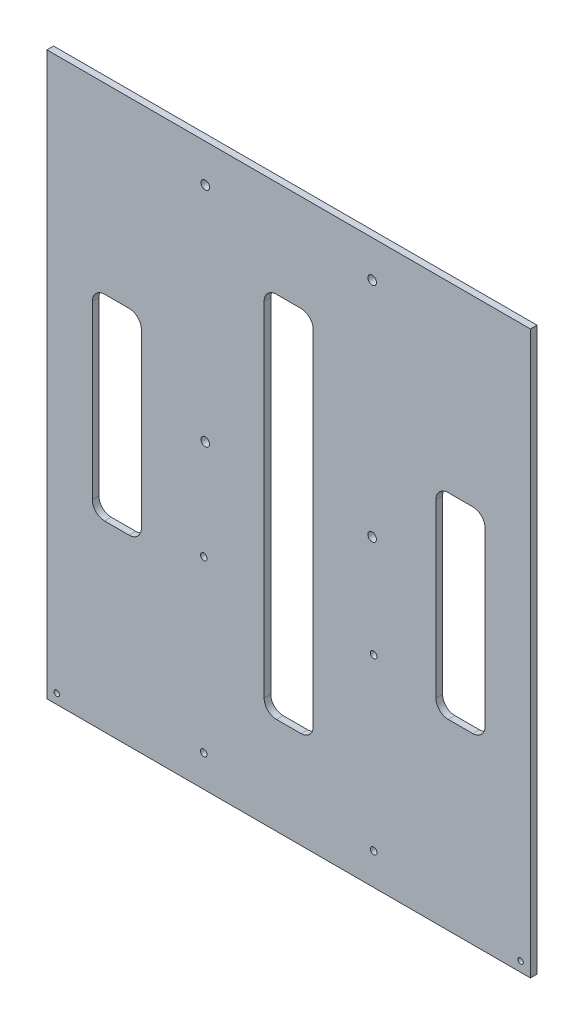
SolidWorks part; units mm, degrees
ref_plane "前视基准面" through (0, 0, 0) normal (0, 0, 1) x (1, 0, 0)
ref_plane "上视基准面" through (0, 0, 0) normal (0, 1, 0) x (1, 0, 0)
ref_plane "右视基准面" through (0, 0, 0) normal (1, 0, 0) x (0, 0, -1)
other "Configuration Table"
sketch "草图1" plane through (0, 0, 0) normal (0, 0, 1) x (1, 0, 0)
  line L1 (0, 0) -> (197, 0)
  line L2 (0, 0) -> (0, 229)
  line L3 (0, 229) -> (197, 229)
  line L4 (197, 0) -> (197, 229)
  line L5 (0, 0) -> (197, 229) construction
  line L6 (0, 229) -> (197, 0) construction
  point P4 (98.5, 114.5)
  dimension "D1" = 197
  dimension "D2" = 229
extrude "凸台-拉伸1" add sketch "草图1" along normal blind 2.7
sketch "草图2" plane through (0, 0, 2.7) normal (0, 0, 1) x (1, 0, 0)
  line L0 (0, 0) -> (197, 0) construction
  line L1 (0, 229) -> (0, 0) construction
  line L2 (197, 0) -> (197, 229) construction
  circle A0 centre (4, 4) radius 1.1
  circle A1 centre (4, 4) radius 2.5 construction
  circle A2 centre (193, 4) radius 1.1
  dimension "D1" = 2.2
  dimension "D4" = 5
  dimension "D5" = 2.2
  dimension "D2" = 4
  dimension "D3" = 4
  dimension "D6" = 4
  dimension "D7" = 4
extrude "切除-拉伸1" cut sketch "草图2" against normal blind 2.85
sketch "草图3" plane through (0, 0, 0) normal (0, 0, -1) x (-1, 0, 0)
  line L0 (-98.5, 229) -> (-98.5, 0) construction
  line L1 (-197, 114.5) -> (0, 114.5) construction
  line L2 (-133.1, 12.9) -> (-63.9, 12.9) construction
  line L3 (-136, 85) -> (-61, 85) construction
  line L4 (0, 0) -> (0, 229)
  line L5 (0, 229) -> (-197, 229)
  line L6 (-197, 229) -> (-197, 0)
  line L7 (-197, 0) -> (0, 0)
  line L8 (0, 0) -> (0, 229) construction
  line L9 (0, 229) -> (-197, 229) construction
  line L10 (-197, 229) -> (-197, 0) construction
  line L11 (-197, 0) -> (0, 0) construction
  line L12 (-136, 85) -> (-136, 10) construction
  line L13 (-136, 10) -> (-61, 10) construction
  line L14 (-61, 85) -> (-61, 10) construction
  line L15 (-136, 85) -> (-61, 10) construction
  line L16 (-136, 10) -> (-61, 85) construction
  circle A0 centre (-133.1, 12.9) radius 1.35
  circle A1 centre (-133.1, 82.1) radius 1.35
  circle A2 centre (-63.9, 82.1) radius 1.35
  circle A3 centre (-63.9, 12.9) radius 1.35
  point P12 (-98.5, 47.5)
  point P21 (-98.5, 12.9)
  dimension "D4" = 2.7
  dimension "D5" = 2.7
  dimension "D6" = 2.7
  dimension "D7" = 2.7
  dimension "D2" = 75
  dimension "D3" = 75
  dimension "D8" = 69.2
  dimension "D9" = 69.2
  dimension "D10" = 69.2
  dimension "D11" = 69.2
  dimension "D12" = 2.9
  dimension "D13" = 2.9
  dimension "D14" = 10
  dimension "D1" = 0
extrude "切除-拉伸2" cut sketch "草图3" against normal blind 9
sketch "草图4" plane through (0, 0, 0) normal (0, 0, -1) x (-1, 0, 0)
  line L0 (-133.1, 27.9) -> (-133.1, 220.1492) construction
  line L1 (-63.9, 12.9) -> (-63.9, 193.6705) construction
sketch "草图5" plane through (0, 0, 0) normal (0, 0, -1) x (-1, 0, 0)
  line L0 (-98.5, 229) -> (-98.5, 0) construction
  line L1 (-197, 229) -> (0, 229) construction
  circle A0 centre (-132.5, 214) radius 1.75
  circle A1 centre (-64.5014, 213.5596) radius 1.75
  circle A2 centre (-132.5, 123.4) radius 1.75
  circle A3 centre (-64.5, 122.9596) radius 1.75
  dimension "D5" = 3.5
  dimension "D6" = 3.5
  dimension "D7" = 3.5
  dimension "D8" = 3.5
  dimension "D1" = 68
  dimension "D2" = 34
  dimension "D3" = 34
  dimension "D4" = 34
  dimension "D9" = 90.6
  dimension "D10" = 90.6
  dimension "D11" = 15
  dimension "D12" = 33.9986
extrude "切除-拉伸3" cut sketch "草图5" against normal blind 10
sketch "草图6" plane through (0, 0, 0) normal (0, 0, -1) x (-1, 0, 0)
  line L0 (-98.5, 229) -> (-98.5, 0) construction
  line L1 (-178.5, 154.5) -> (-158.5, 154.5)
  line L2 (-178.5, 154.5) -> (-178.5, 74.5)
  line L3 (-178.5, 74.5) -> (-158.5, 74.5)
  line L4 (-158.5, 154.5) -> (-158.5, 74.5)
  line L5 (-178.5, 154.5) -> (-158.5, 74.5) construction
  line L6 (-178.5, 74.5) -> (-158.5, 154.5) construction
  line L7 (-38.5, 154.5) -> (-18.5, 154.5)
  line L8 (-38.5, 154.5) -> (-38.5, 74.5)
  line L9 (-38.5, 74.5) -> (-18.5, 74.5)
  line L10 (-18.5, 154.5) -> (-18.5, 74.5)
  line L11 (-38.5, 154.5) -> (-18.5, 74.5) construction
  line L12 (-38.5, 74.5) -> (-18.5, 154.5) construction
  line L13 (-108.5, 189.5) -> (-88.5, 189.5)
  line L14 (-108.5, 189.5) -> (-108.5, 39.5)
  line L15 (-108.5, 39.5) -> (-88.5, 39.5)
  line L16 (-88.5, 189.5) -> (-88.5, 39.5)
  line L17 (-108.5, 189.5) -> (-88.5, 39.5) construction
  line L18 (-108.5, 39.5) -> (-88.5, 189.5) construction
  line L19 (-197, 229) -> (0, 229) construction
  line L20 (0, 0) -> (-197, 0) construction
  line L21 (-197, 114.5) -> (0, 114.5) construction
  line L22 (-197, 0) -> (-197, 229) construction
  line L23 (0, 229) -> (0, 0) construction
  point P4 (-168.5, 114.5)
  point P9 (-28.5, 114.5)
  point P14 (-98.5, 114.5)
  point P21 (0, 0)
  dimension "D1" = 70
  dimension "D2" = 70
  dimension "D3" = 20
  dimension "D4" = 20
  dimension "D5" = 80
  dimension "D6" = 80
  dimension "D7" = 150
  dimension "D8" = 20
extrude "切除-拉伸4" cut sketch "草图6" against normal blind 10
fillet "圆角1" radius 5 12 edges at (88.5, 39.5, 1.35) (108.5, 39.5, 1.35) (108.5, 189.5, 1.35) (18.5, 154.5, 1.35) (18.5, 74.5, 1.35) (38.5, 74.5, 1.35) (38.5, 154.5, 1.35) (158.5, 154.5, 1.35) (158.5, 74.5, 1.35) (178.5, 74.5, 1.35) (178.5, 154.5, 1.35) (88.5, 189.5, 1.35)
